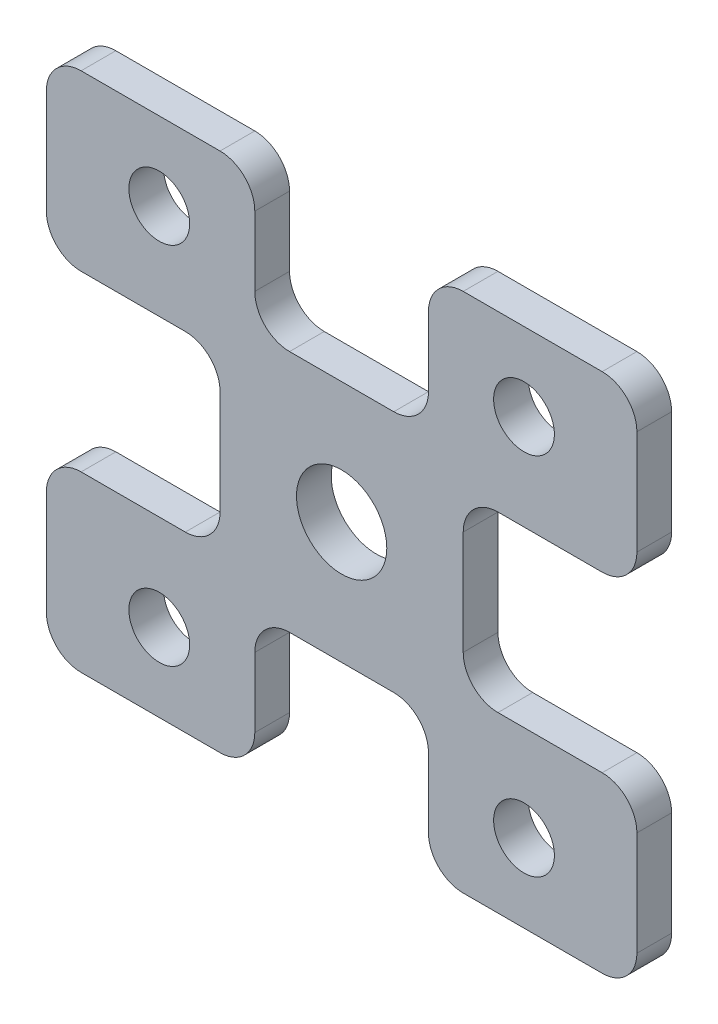
SolidWorks part; units mm, degrees
material "尼龙 101"
ref_plane "前视基准面" through (0, 0, 0) normal (0, 0, 1) x (1, 0, 0)
ref_plane "上视基准面" through (0, 0, 0) normal (0, 1, 0) x (1, 0, 0)
ref_plane "右视基准面" through (0, 0, 0) normal (1, 0, 0) x (0, 0, -1)
sketch "草图1" plane through (0, 0, 0) normal (0, 0, 1) x (1, 0, 0)
  line L1 (-17, -15) -> (17, -15)
  line L2 (-17, -15) -> (-17, 15)
  line L3 (-17, 15) -> (17, 15)
  line L4 (17, -15) -> (17, 15)
  line L5 (-17, -15) -> (17, 15) construction
  line L6 (-17, 15) -> (17, -15) construction
  circle A0 centre (0, 0) radius 2.6
  point P0 (0, 0)
  dimension "D3" = 5.2
  dimension "D1" = 30
  dimension "D2" = 34
extrude "凸台-拉伸1" add sketch "草图1" along normal blind 2
sketch "草图2" plane through (0, 0, 0) normal (0, 0, -1) x (-1, 0, 0)
  circle A0 centre (10.5, -10.5) radius 1.75
  circle A1 centre (-10.5, -10.5) radius 1.75
  circle A2 centre (-10.5, 10.5) radius 1.75
  circle A3 centre (10.5, 10.5) radius 1.75
  dimension "D1" = 3.5
  dimension "D2" = 3.5
  dimension "D3" = 3.5
  dimension "D4" = 3.5
extrude "切除-拉伸1" cut sketch "草图2" against normal blind 2
sketch "草图3" plane through (0, 0, 2) normal (0, 0, 1) x (1, 0, 0)
  line L0 (-17, 5) -> (-7, 5)
  line L1 (-17, 15) -> (-17, -15) construction
  line L2 (-7, 5) -> (-7, -5)
  line L3 (-7, -5) -> (-17, -5)
  line L4 (-17, -5) -> (-17, 5)
  line L5 (-17, 0) -> (0, 0) construction
  line L6 (0, 9) -> (0, 0) construction
  line L8 (-17, -15) -> (17, -15) construction
  line L9 (-5, 7) -> (-5, 17)
  line L10 (-5, 17) -> (5, 17)
  line L11 (5, 7) -> (-5, 7)
  line L12 (5, 17) -> (5, 7)
  line L13 (7, 5) -> (17, 5)
  line L14 (17, 5) -> (17, -5)
  line L15 (7, -5) -> (7, 5)
  line L16 (17, -5) -> (7, -5)
  line L17 (5, -7) -> (5, -17)
  line L18 (5, -17) -> (-5, -17)
  line L19 (-5, -7) -> (5, -7)
  line L20 (-5, -17) -> (-5, -7)
  line L26 (19, 0) -> (19.92, 0) construction
  line L36 (0, -9) -> (0, -15) construction
  point P35 (0, 0)
  point P38 (0, 0)
  dimension "D1" = 10
  dimension "D2" = 10
  dimension "D3" = 0
  dimension "D4" = 4
extrude "切除-拉伸2" cut sketch "草图3" against normal blind 2
fillet "圆角1" radius 2 20 edges at (-17, -15, 1) (17, -15, 1) (17, 15, 1) (-17, 15, 1) (5, 7, 1) (-5, 7, 1) (7, 5, 1) (7, -5, 1) (5, -7, 1) (-5, -7, 1) (-7, -5, 1) (-7, 5, 1) (5, -15, 1) (-5, -15, 1) (17, -5, 1) (17, 5, 1) (5, 15, 1) (-5, 15, 1) (-17, 5, 1) (-17, -5, 1)
fillet "圆角2" [suppressed] radius 5
